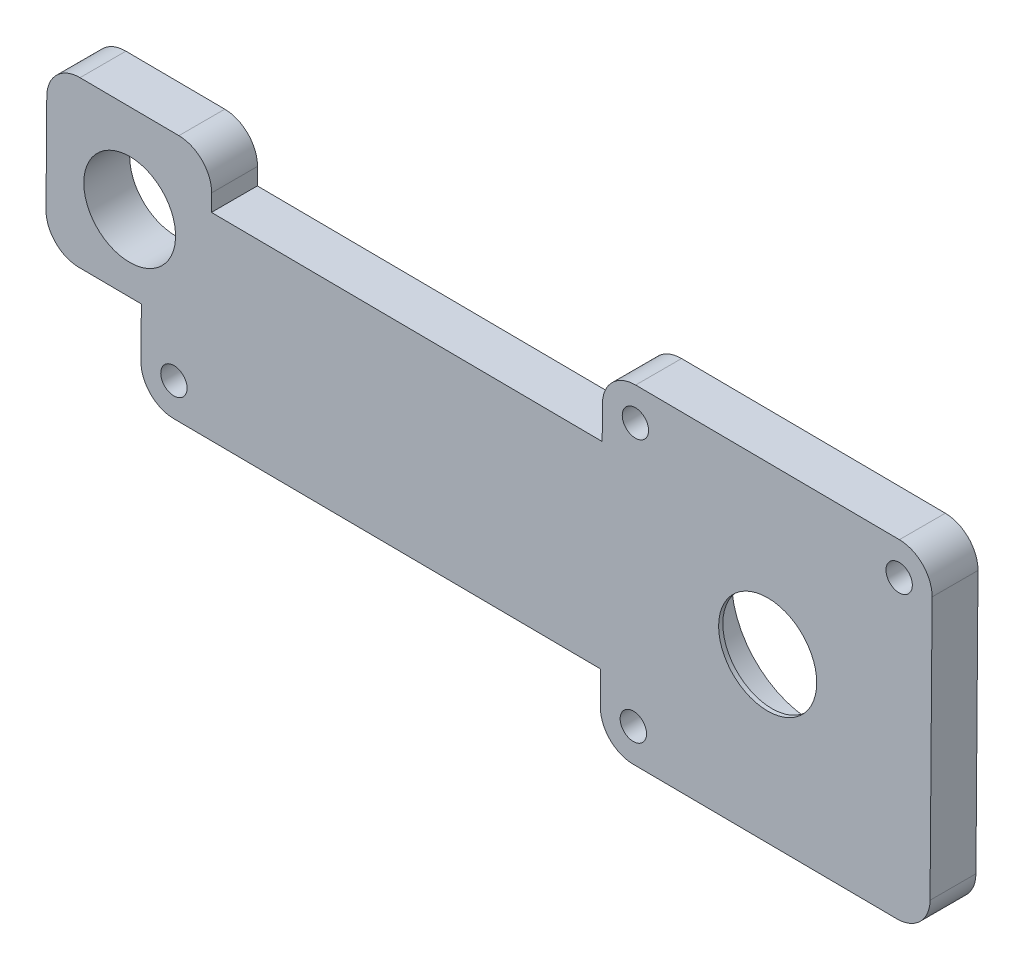
SolidWorks part; units mm, degrees
ref_plane "Front Plane" through (0, 0, 0) normal (0, 0, 1) x (1, 0, 0)
ref_plane "Top Plane" through (0, 0, 0) normal (0, 1, 0) x (1, 0, 0)
ref_plane "Right Plane" through (0, 0, 0) normal (1, 0, 0) x (0, 0, -1)
sketch "Sketch10" plane through (0, 0, 0) normal (0, 0, -1) x (-1, 0, 0)
  line L0 (-33.3871, 0.4566) -> (-54.6821, 21.7516) construction
  line L2 (-52.2874, 19.3569) -> (-52.2874, -15.6781) construction
  line L3 (11.8635, 18.2366) -> (-9.2571, 18.2366) construction
  line L4 (-9.2571, 18.2366) -> (1.3032, 23.5942) construction
  line L5 (1.3032, 23.5942) -> (1.3032, -17.7894) construction
  line L6 (2.4777, 0.4566) -> (-12.3051, 0.4566) construction
  line L7 (28.056, 6.8519) -> (41.4135, 20.2095) construction
  circle A0 centre (-33.3871, 0.4566) radius 4.7244
  circle A2 centre (-52.2874, -15.6781) radius 1.905
  circle A4 centre (28.056, 6.8519) radius 1.1793
  circle A5 centre (37.4743, 16.2702) radius 1.905
  circle A6 centre (-13.8463, 13.5969) radius 1.905
  circle A7 centre (-13.8463, -12.6838) radius 1.905
  circle A10 centre (27.2212, -14.6226) radius 2.032
  circle A11 centre (-50.815, 17.8845) radius 1.905
  circle A12 centre (16.4527, 13.5969) radius 1.905
sketch "Sketch4" plane through (0, 0, 0) normal (0, 0, 1) x (1, 0, 0)
  line L60 (17.3013, -8.8059) -> (17.2764, -11.9808)
  line L61 (20.4263, -15.1807) -> (45.8256, -15.3803)
  line L62 (49.0254, -12.2303) -> (49.225, 13.1689)
  line L63 (46.075, 16.3688) -> (20.6758, 16.5683)
  line L64 (17.476, 13.4184) -> (17.451, 10.2435)
  line L65 (17.451, 10.2435) -> (-20.1784, 10.5391)
  line L66 (-20.1784, 10.5391) -> (-20.1656, 12.1719)
  line L67 (-23.3155, 15.3718) -> (-32.8402, 15.4466)
  line L68 (-36.0401, 12.2966) -> (-36.1149, 2.7719)
  line L69 (-32.9649, -0.4279) -> (-26.9322, -0.4753)
  line L70 (-26.9322, -0.4753) -> (-26.9699, -5.283)
  line L71 (-23.82, -8.4828) -> (17.3013, -8.8059)
  circle A13 centre (33.3871, 0.4566) radius 4.7244
  arc A51 (17.2764, -11.9808) -> (20.4263, -15.1807) centre (20.4513, -12.0058) ccw
  arc A52 (45.8256, -15.3803) -> (49.0254, -12.2303) centre (45.8505, -12.2054) ccw
  arc A53 (49.225, 13.1689) -> (46.075, 16.3688) centre (46.0501, 13.1939) ccw
  arc A54 (20.6758, 16.5683) -> (17.476, 13.4184) centre (20.6509, 13.3934) ccw
  arc A55 (-20.1656, 12.1719) -> (-23.3155, 15.3718) centre (-23.3405, 12.1969) ccw
  arc A56 (-32.8402, 15.4466) -> (-36.0401, 12.2966) centre (-32.8652, 12.2717) ccw
  arc A57 (-36.1149, 2.7719) -> (-32.9649, -0.4279) centre (-32.94, 2.747) ccw
  arc A58 (-26.9699, -5.283) -> (-23.82, -8.4828) centre (-23.795, -5.3079) ccw
extrude "Stock" add sketch "Sketch4" along normal blind 4.4196 separate body
sketch "Sketch7" plane through (0, 0, 0) normal (0, 0, -1) x (-1, 0, 0)
  circle A0 centre (-33.3871, 0.4566) radius 7.8994
  dimension "D1" = 15.7988
extrude "CV Gear Well" cut sketch "Sketch7" against normal blind 4.0132
sketch "Sketch8" plane through (0, 0, 0) normal (0, 0, -1) x (-1, 0, 0)
  circle A0 centre (-12.3051, 0.4566) radius 2.2987
  circle A1 centre (2.4777, 0.4566) radius 2.2987
  circle A2 centre (17.2605, 0.4566) radius 2.2987
  dimension "D1" = 4.5974
extrude "Idler Gear Well" cut sketch "Sketch8" against normal blind 4.2926
sketch "Sketch9" plane through (0, 0, 0) normal (0, 0, -1) x (-1, 0, 0)
  circle A0 centre (28.056, 6.8519) radius 4.4196
  circle A1 centre (-46.0501, 13.1939) radius 1.27
  circle A2 centre (-20.6509, 13.3934) radius 1.27
  circle A3 centre (-20.4513, -12.0058) radius 1.27
  circle A4 centre (23.795, -5.3079) radius 1.27
  dimension "D1" = 8.8392
  dimension "D2" = 2.54
extrude "Outdrive Gear Well" cut sketch "Sketch9" against normal blind 4.4196
